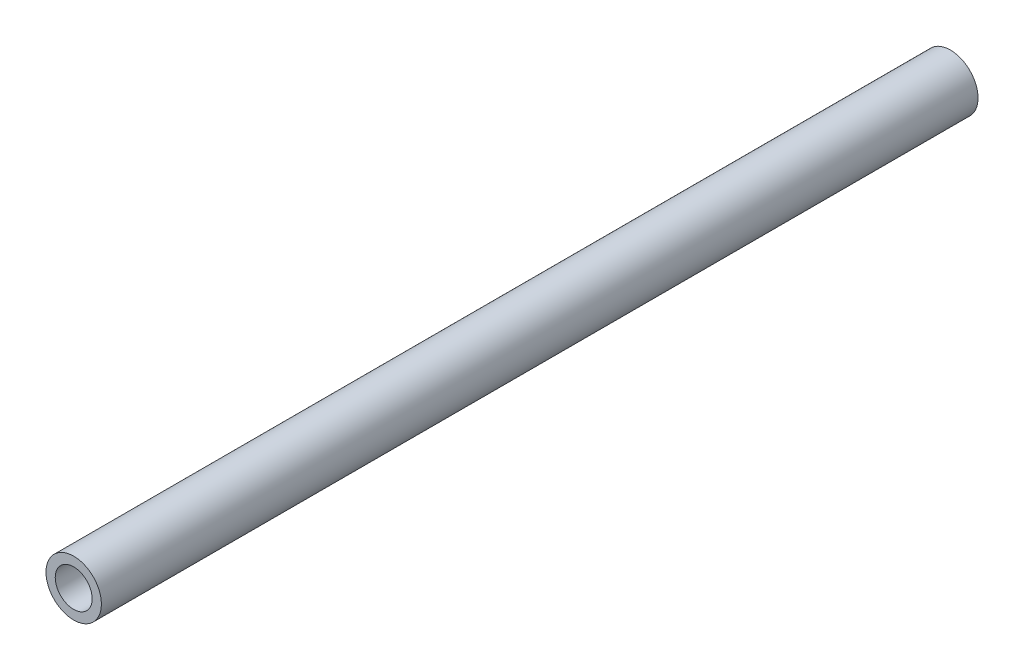
SolidWorks part; units mm, degrees
ref_plane "Front Plane" through (0, 0, 0) normal (0, 0, 1) x (1, 0, 0)
ref_plane "Top Plane" through (0, 0, 0) normal (0, 1, 0) x (1, 0, 0)
ref_plane "Right Plane" through (0, 0, 0) normal (1, 0, 0) x (0, 0, -1)
sketch "Pole Cross Section Sketch" plane through (0, 0, 0) normal (0, 0, 1) x (1, 0, 0)
  circle A0 centre (0, 0) radius 30
  circle A1 centre (0, 0) radius 20
  dimension "D1" = 60
  dimension "D2" = 40
extrude "Pipe Extrude" add sketch "Pole Cross Section Sketch" along normal blind 950
